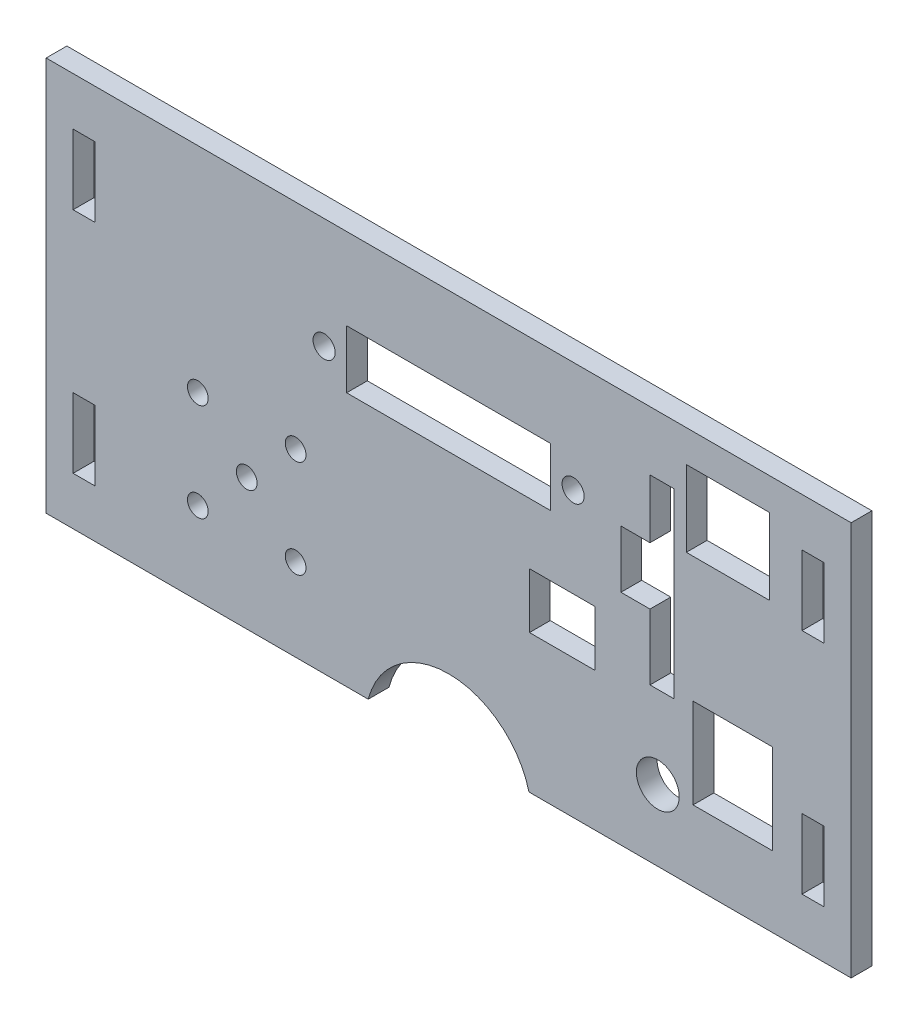
SolidWorks part; units mm, degrees
ref_plane "Front Plane" through (0, 0, 0) normal (0, 0, 1) x (1, 0, 0)
ref_plane "Top Plane" through (0, 0, 0) normal (0, 1, 0) x (1, 0, 0)
ref_plane "Right Plane" through (0, 0, 0) normal (1, 0, 0) x (0, 0, -1)
sketch "Sketch1" plane through (0, 0, 0) normal (0, 0, 1) x (1, 0, 0)
  line L0 (-54.19, 0) -> (-54.19, 18.4259) construction
  line L3 (-58.19, 60) -> (58.19, 60)
  line L5 (0, 0) -> (0, 62.6748) construction
  line L6 (0, 75) -> (0, 63) construction
  line L18 (-58.19, 3) -> (-11.619, 3)
  line L26 (-58.19, 3) -> (-58.19, 60)
  line L27 (58.19, 3) -> (58.19, 60)
  line L66 (58.19, 3) -> (11.619, 3)
  arc A0 (-11.619, 3) -> (11.619, 3) centre (0, 0) cw
  point P2 (0, 60)
  line B0 (-54.29, 9.95) -> (-54.29, 20.05)
  line B1 (-54.29, 9.95) -> (-51.09, 9.95)
  line B2 (-51.09, 9.95) -> (-51.09, 20.05)
  line B3 (-54.29, 20.05) -> (-51.09, 20.05)
  line B4 (-54.29, 42.95) -> (-54.29, 53.05)
  line B5 (-54.29, 42.95) -> (-51.09, 42.95)
  line B6 (-51.09, 42.95) -> (-51.09, 53.05)
  line B7 (-54.29, 53.05) -> (-51.09, 53.05)
  line B8 (54.29, 9.95) -> (54.29, 20.05)
  line B9 (54.29, 9.95) -> (51.09, 9.95)
  line B10 (51.09, 9.95) -> (51.09, 20.05)
  line B11 (54.29, 20.05) -> (51.09, 20.05)
  line B12 (54.29, 42.95) -> (54.29, 53.05)
  line B13 (54.29, 42.95) -> (51.09, 42.95)
  line B14 (51.09, 42.95) -> (51.09, 53.05)
  line B15 (54.29, 53.05) -> (51.09, 53.05)
  dimension "D7" = 12
  dimension "D1" = 4
sketch_block_instance "external-tooth-slot-1"
sketch_block "external-tooth-slot" parameters "D1"=10.1, "D2"=3.2, "D3"=9.7492, "D4"=9.7492, "D5"=3.2
sketch_block_instance "external-tooth-slot-3"
sketch_block_instance "external-tooth-slot-4"
sketch_block_instance "external-tooth-slot-5"
extrude "Boss-Extrude1" add sketch "Sketch1" against normal up to vertex (3 mm away)
sketch "Sketch2"
  line L0 (-18, 44) -> (18, 44) construction
  line L1 (11.69, 31) -> (21.19, 31)
  line L2 (11.69, 31) -> (11.69, 23)
  line L3 (11.69, 23) -> (21.19, 23)
  line L4 (21.19, 31) -> (21.19, 23)
  line L5 (-14.75, 48.2) -> (14.75, 48.2)
  line L6 (-14.75, 48.2) -> (-14.75, 39.8)
  line L7 (-14.75, 39.8) -> (14.75, 39.8)
  line L8 (14.75, 48.2) -> (14.75, 39.8)
  line L9 (24.9122, 42.9551) -> (29.1122, 42.9551)
  line L10 (24.9122, 42.9551) -> (24.9122, 34.6551)
  line L11 (24.9122, 34.6551) -> (29.1122, 34.6551)
  line L12 (29.1122, 42.9551) -> (29.1122, 51.4551)
  line L13 (0, 39.8) -> (0, 48.2) construction
  line L14 (58.19, 60) -> (-58.19, 60) construction
  line L15 (0, 0) -> (0, 32.5647) construction
  line L16 (58.19, 60) -> (-58.19, 60) construction
  line L17 (-45.44, 22) -> (-12.94, 22) construction
  line L18 (58.19, 3) -> (58.19, 60) construction
  line L19 (35.3406, 26.2459) -> (46.8406, 26.2459)
  line L20 (35.3406, 26.2459) -> (35.3406, 13.2459)
  line L21 (35.3406, 13.2459) -> (46.8406, 13.2459)
  line L22 (46.8406, 26.2459) -> (46.8406, 13.2459)
  line L23 (-29.19, 38.25) -> (-29.19, 5.75) construction
  line L24 (-36.2611, 14.9289) -> (-36.2611, 29.0711) construction
  line L25 (-36.2611, 29.0711) -> (-22.1189, 29.0711) construction
  line L26 (29.1122, 51.4551) -> (32.6122, 51.4551)
  line L27 (-51.19, 0) -> (51.19, 0) construction
  line L28 (11.619, 3) -> (58.19, 3) construction
  line L29 (32.6122, 51.4551) -> (32.6122, 25.1551)
  line L30 (32.6122, 25.1551) -> (29.1122, 25.1551)
  line L31 (46.3622, 44.3807) -> (34.3622, 44.3807)
  line L32 (46.3622, 44.3807) -> (46.3622, 55.3807)
  line L33 (46.3622, 55.3807) -> (34.3622, 55.3807)
  line L34 (34.3622, 44.3807) -> (34.3622, 55.3807)
  line L35 (29.1122, 25.1551) -> (29.1122, 34.6551)
  circle A0 centre (-18, 44) radius 1.6
  circle A1 centre (18, 44) radius 1.6
  circle A2 centre (-29.19, 22) radius 16.25 construction
  circle A3 centre (-22.1189, 29.0711) radius 1.5
  circle A4 centre (-36.2611, 29.0711) radius 1.5
  circle A5 centre (-36.2611, 14.9289) radius 1.5
  circle A6 centre (-22.1189, 14.9289) radius 1.5
  circle A7 centre (-29.19, 22) radius 1.5
  circle A8 centre (-29.19, 22) radius 10 construction
  circle A9 centre (30.2406, 13.2459) radius 3.1
other "AlignGroup1" parameters "D1"=3.187, "D10"=31.4022, "D11"=3.7782, "D16"=21.7186, "D31"=7.7919, "D33"=6.2, "D2"=33.6225, "D3"=9.5609, "D4"=7.0113, "D5"=102.18, "D6"=5.5772, "D7"=3.9837, "D8"=4.6211, "D9"=5.2585, "D12"=102.18, "D13"=14, "D14"=14.0468, "D15"=15.6011, "D17"=22.9, "D18"=102.18, "D19"=39.09, "D20"=10.1, "D21"=32.5647, "D22"=4.6193, "D23"=17.0449, "D24"=33.7541, "D25"=0, "D26"=11.8278, "D27"=27.6854, "D28"=11.3494, "D29"=1.25, "D30"=7.6781, "D32"=46.7541
other "AlignGroup2"
extrude "sensor mounting holes" cut sketch "Sketch2" against normal up to next
